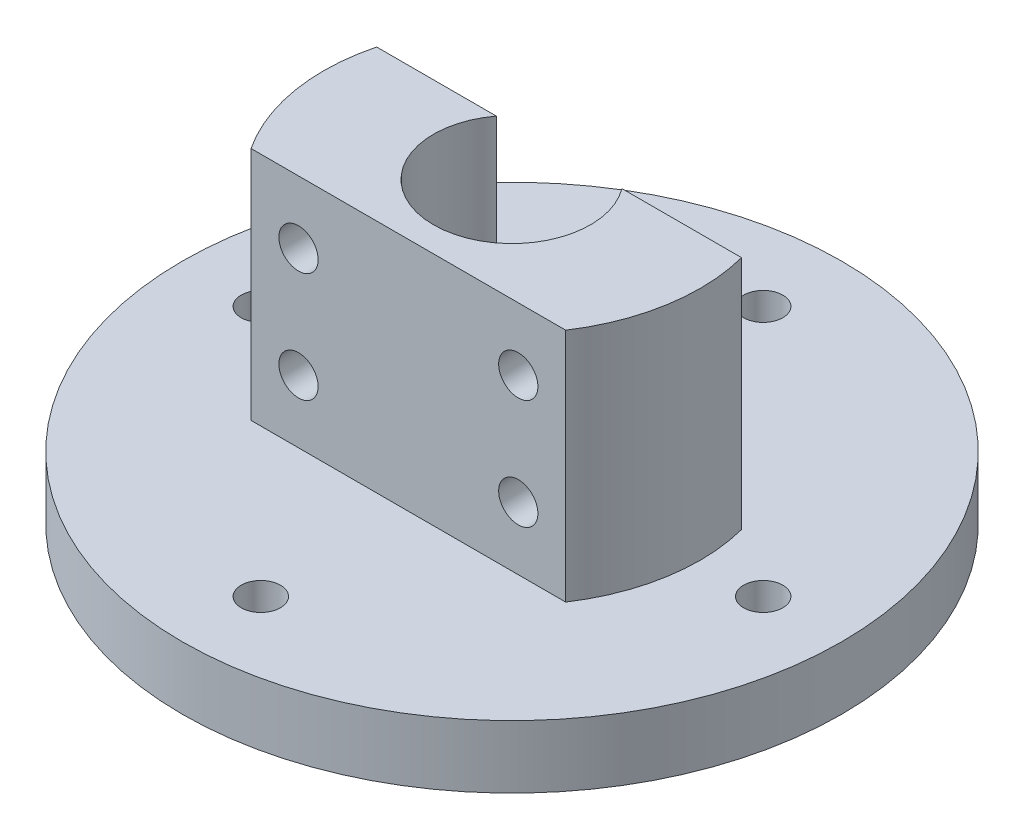
SolidWorks part; units mm, degrees
material "6061 合金"
ref_plane "前视基准面" through (0, 0, 0) normal (0, 0, 1) x (1, 0, 0)
ref_plane "上视基准面" through (0, 0, 0) normal (0, 1, 0) x (1, 0, 0)
ref_plane "右视基准面" through (0, 0, 0) normal (1, 0, 0) x (0, 0, -1)
other "Configuration Table"
sketch "草图1" plane through (0, 0, 0) normal (0, 1, 0) x (1, 0, 0)
  circle A0 centre (0, 0) radius 21
  circle A1 centre (0, 0) radius 16 construction
  circle A2 centre (0, 16) radius 1.25 construction
  circle A3 centre (16, 0) radius 1.25 construction
  circle A4 centre (0, -16) radius 1.25 construction
  circle A5 centre (-16, 0) radius 1.25 construction
  dimension "D1" = 42
  dimension "D2" = 32
  dimension "D3" = 2.5
  dimension "D4" = 4
extrude "凸台-拉伸1" add sketch "草图1" along normal blind 4
hole_wizard "M3 螺纹孔1" positions "草图3" profile "草图4" tap size "M3" standard "GB" end condition through all
sketch "草图3" plane through (0, 4, 0) normal (0, 1, 0) x (1, 0, 0)
  point P0 (0, 16)
  point P3 (16, 0)
  point P6 (0, -16)
  point P9 (-16, 0)
sketch "草图4" plane through (0, 4, -16) normal (1, 0, 0) x (0, 0, 1)
  line L0 (0, 0) -> (0, 4)
  line L1 (0, 4) -> (1.25, 4)
  line L2 (1.25, 4) -> (1.25, 0)
  line L5 (1.25, 0) -> (0, 0)
  line L11 (0, -6.35) -> (0, 107.95) construction
  dimension "通孔螺纹孔钻头直径" = 2.5
  dimension "通孔螺纹孔钻头深度" = 4
cosmetic thread "孔螺纹线1" parameters "D2"=3
cosmetic thread "孔螺纹线2" parameters "D2"=3
cosmetic thread "孔螺纹线3" parameters "D2"=3
cosmetic thread "孔螺纹线4" parameters "D2"=3
sketch "草图2" plane through (0, 4, 0) normal (0, 1, 0) x (1, 0, 0)
  line L0 (-11.619, 3) -> (11.619, 3)
  line L1 (-10.022, -6.6) -> (10.022, -6.6)
  arc A0 (-11.619, 3) -> (-10.022, -6.6) centre (0, 0) ccw
  arc A2 (10.022, -6.6) -> (11.619, 3) centre (0, 0) ccw
  dimension "D1" = 24
  dimension "D2" = 3
  dimension "D3" = 6.6
extrude "凸台-拉伸2" add sketch "草图2" along normal blind 15
sketch "草图5" plane through (0, 19, 0) normal (0, 1, 0) x (1, 0, 0)
  circle A0 centre (0, 0) radius 5
  dimension "D1" = 10
extrude "切除-拉伸1" cut sketch "草图5" against normal through all
sketch "草图6" plane through (0, 0, -3) normal (0, 0, -1) x (-1, 0, 0)
  line L0 (0, 19) -> (0, 4) construction
  line L1 (5, 19) -> (-5, 19) construction
  line L2 (21, 4) -> (-21, 4) construction
  line L3 (4, 4) -> (11.619, 4) construction
  line L4 (-7, 8) -> (7, 8) construction
  line L5 (-7, 8) -> (-7, 15) construction
  line L6 (-7, 15) -> (7, 15) construction
  line L7 (7, 8) -> (7, 15) construction
  line L8 (-7, 8) -> (7, 15) construction
  line L9 (-7, 15) -> (7, 8) construction
  point P6 (0, 11.5)
  point P7 (7, 15)
  point P8 (-7, 8)
  point P9 (-7, 15)
  point P10 (7, 8)
  dimension "D1" = 14
  dimension "D2" = 4
  dimension "D3" = 7
hole_wizard "M3 螺纹孔2" positions "草图6" profile "草图7" tap size "M3" standard "GB"
sketch "草图7" plane through (-7, 8, -3) normal (1, 0, 0) x (0, 1, 0)
  line L0 (0, 0) -> (0, 24)
  line L1 (0, 24) -> (1.25, 24)
  line L2 (1.25, 24) -> (1.25, 0)
  line L5 (1.25, 0) -> (0, 0)
  line L11 (0, -6.35) -> (0, 107.95) construction
  dimension "通孔螺纹孔钻头直径" = 2.5
  dimension "通孔螺纹孔钻头深度" = 24
cosmetic thread "孔螺纹线5" parameters "D2"=3
cosmetic thread "孔螺纹线6" parameters "D2"=3
cosmetic thread "孔螺纹线7" parameters "D2"=3
cosmetic thread "孔螺纹线8" parameters "D2"=3
